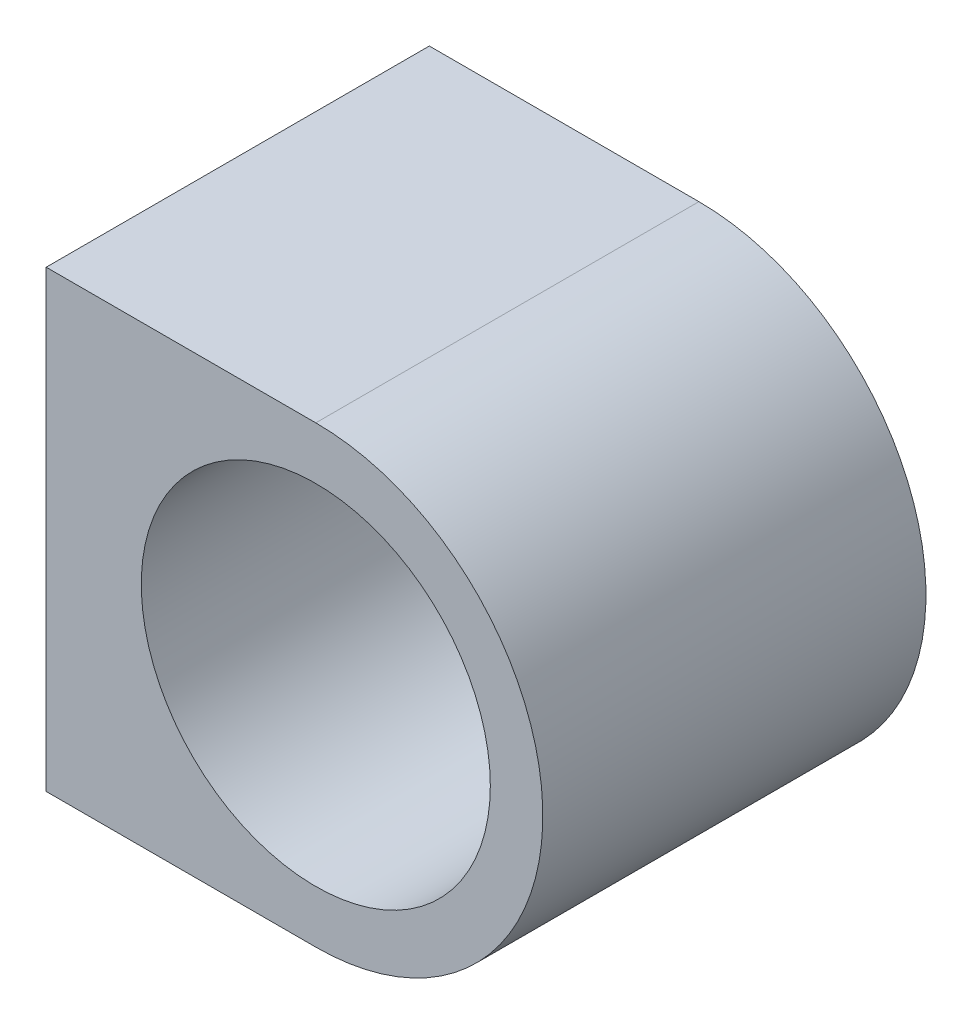
SolidWorks part; units mm, degrees
ref_plane "Front Plane" through (0, 0, 0) normal (0, 0, 1) x (1, 0, 0)
ref_plane "Top Plane" through (0, 0, 0) normal (0, 1, 0) x (1, 0, 0)
ref_plane "Right Plane" through (0, 0, 0) normal (1, 0, 0) x (0, 0, -1)
sketch "Sketch1" plane through (0, 0, 0) normal (0, 0, 1) x (1, 0, 0)
  line L0 (-9.5, 8) -> (-9.5, -8)
  line L1 (0, 8) -> (-9.5, 8)
  line L2 (0, -8) -> (-9.5, -8)
  circle A3 centre (0, 0) radius 6.15
  arc A4 (0, -8) -> (0, 8) centre (0, 0) ccw
  dimension "D1" = 12.3
  dimension "D2" = 16
  dimension "D3" = 9.5
extrude "Boss-Extrude1" add sketch "Sketch1" along normal blind 13.5
hole_wizard "Ø2.7 (2.7) Diameter Hole1" positions "Sketch5" profile "Sketch4" hole size "Ø2.7" standard "Ansi Metric"
sketch "Sketch5" plane through (-9.5, 0, 0) normal (-1, 0, 0) x (0, 0, 1)
  line L1 (2.5, -5) -> (11, -5) construction
  line L2 (2.5, -5) -> (2.5, 5) construction
  line L3 (2.5, 5) -> (11, 5) construction
  line L4 (11, -5) -> (11, 5) construction
  line L5 (0, 0) -> (2.5, 0) construction
  line L7 (0, 8) -> (0, -8) construction
  line L10 (13.5, 0) -> (11, 0) construction
  line L11 (13.5, 8) -> (13.5, -8) construction
  point P0 (2.5, -5)
  point P89 (2.5, 5)
  point P91 (11, 5)
  point P93 (11, -5)
  dimension "D1" = 2.5
  dimension "D2" = 10
sketch "Sketch4" plane through (-9.5, -5, 2.5) normal (0, 1, 0) x (0, 0, 1)
  line L0 (0, 0) -> (0, 4.8112)
  line L1 (0, 4.8112) -> (1.35, 4)
  line L2 (1.35, 4) -> (1.35, 0)
  line L5 (1.35, 0) -> (0, 0)
  line L10 (0, 4.8112) -> (-1.35, 4) construction
  line L11 (0, -6.35) -> (0, 107.95) construction
  dimension "Hole Dia." = 2.7
  dimension "Hole Depth" = 4
  dimension "Drill Angle" = 118
